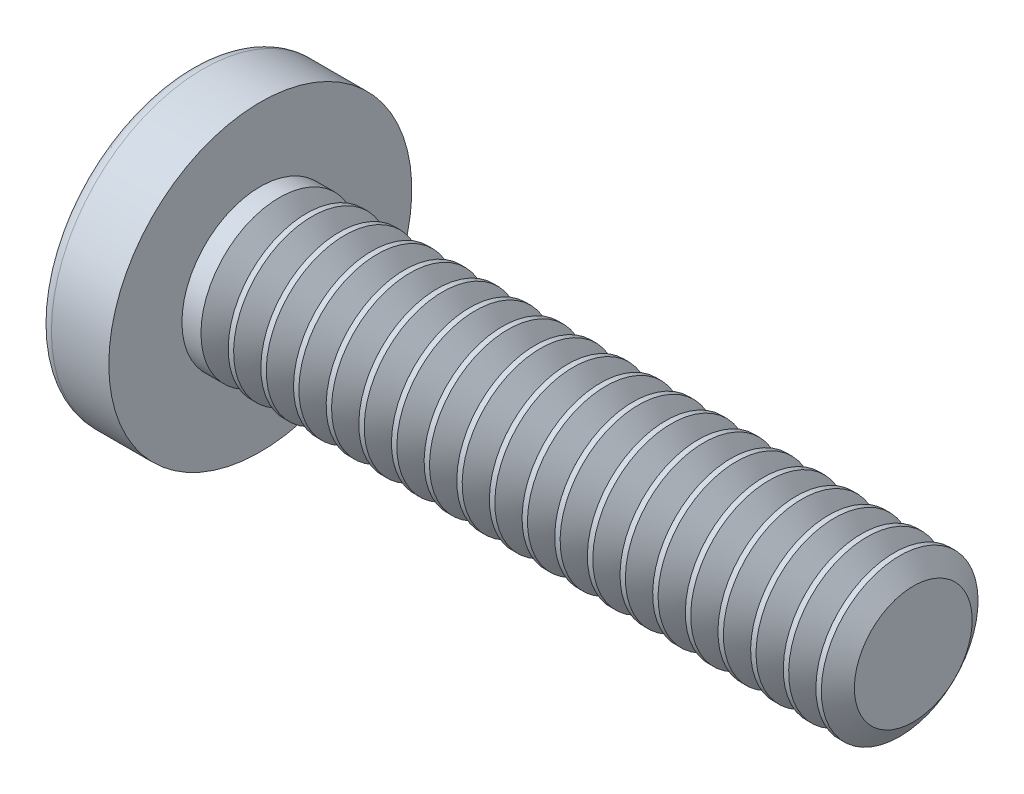
SolidWorks part; units mm, degrees
ref_plane "Plane1" through (0, 0, 0) normal (0, 0, 1) x (1, 0, 0)
ref_plane "Plane2" through (0, 0, 0) normal (0, 1, 0) x (1, 0, 0)
ref_plane "Plane3" through (0, 0, 0) normal (1, 0, 0) x (0, 0, -1)
other "Configuration Table"
sketch "BodySke" plane through (0, 0, 0) normal (0, 0, 1) x (1, 0, 0)
  line L0 (1.1176, 0.762) -> (1.1176, 1.4732)
  line L1 (1.2763, 6.35) -> (1.2764, -3.175) construction
  line L2 (-25.4, 0) -> (127, 0) construction
  line L3 (7.4676, 0) -> (0, 0)
  line L4 (1.1176, 0.762) -> (7.4676, 0.762)
  line L5 (7.4676, 0.762) -> (7.4676, 0)
  line L6 (0.5595, 1.4732) -> (1.1176, 1.4732)
  line L7 (1.1176, -0.762) -> (7.4676, -0.762) construction
  line L8 (1.1176, 6.35) -> (1.1176, -3.175) construction
  arc A0 (0.4562, 1.4202) -> (0, 0) centre (2.4384, 0) ccw
  arc A2 (0.4562, 1.4202) -> (0.5595, 1.4732) centre (0.5595, 1.3462) cw
  dimension "Head_crown_rad" = 2.4384
  dimension "Head_fillet_rad" = 0.127
  dimension "Diameter" = 1.524
  dimension "Length" = 6.35
  dimension "Head_ht" = 1.1176
  dimension "Head_dia" = 2.9464
  dimension "Advance" = 0.3175
  dimension "Thread_nom" = 6.35
revolve "Base-Revolve" add sketch "BodySke" angle 360 about L2
cosmetic thread "ThreadCosmetic" [suppressed] parameters "Thread_length"=6.0325, "Thread_minor"=1.1455
sketch "Sketch3" plane through (0, 0, 0) normal (1, 0, 0) x (0, 0, -1)
  line L0 (0.2794, -0.9652) -> (-0.2794, -0.9652)
  line L1 (0.2794, -0.9652) -> (0.2794, 0.9652)
  line L2 (-0.2794, 0.9652) -> (0.2794, 0.9652)
  line L3 (-0.2794, 0.9652) -> (-0.2794, -0.9652)
  dimension "Cross_dia" = 1.9304
  dimension "D1" = 0.9652
  dimension "Cross_width" = 0.5588
  dimension "D2" = 0.2794
ref_plane "Plane4" through (0.9652, 0, 0) normal (1, 0, 0) x (0, 0, -1)
sketch "Sketch4" plane through (0.9652, 0, 0) normal (1, 0, 0) x (0, 0, -1)
  line L0 (0.1397, -0.1397) -> (-0.1397, -0.1397)
  line L1 (0.1397, -0.1397) -> (0.1397, 0.1397)
  line L2 (-0.1397, 0.1397) -> (0.1397, 0.1397)
  line L3 (-0.1397, 0.1397) -> (-0.1397, -0.1397)
  dimension "D2" = 0.2794
  dimension "D1" = 0.2794
  dimension "D3" = 0.1397
  dimension "D4" = 0.1397
loft "Cut-Loft1" cut profiles "Sketch3", "Sketch4"
pattern_circular "CirPattern1" count 2 every 90 about axis through (0, 0, 0) along (1, 0, 0) of "Cut-Loft1"
sketch "ThdSchSke" plane through (0, 0, 0) normal (0, 0, 1) x (1, 0, 0)
  line L0 (1.4351, -0.5728) -> (1.3026, -0.762)
  line L1 (1.4351, -0.5728) -> (1.5676, -0.762)
  line L2 (1.5676, -0.762) -> (1.5676, -0.9525)
  line L3 (-3.175, 0) -> (5.1513, 0) construction
  line L5 (1.5676, -0.9525) -> (1.3026, -0.9525)
  line L6 (1.3026, -0.9525) -> (1.3026, -0.762)
  dimension "Diameter" = 1.524
  dimension "SideAngle" = 55
  dimension "VeeAngle" = 70
  dimension "Thread_minor" = 1.1455
  dimension "Overcut" = 1.905
  dimension "Start" = 1.4351
revolve "ThreadSchematic" cut sketch "ThdSchSke" angle 360 about L3
pattern_linear "ThdSchPat" count 20 spacing 0.3175 along (1, 0, 0) of "ThreadSchematic"
equation "\"D1@Sketch3\" = \"Cross_dia@Sketch3\" / 2"
equation "\"D2@Sketch3\" = \"Cross_width@Sketch3\" / 2"
equation "\"D1@Sketch4\" = \"Cross_width@Sketch3\" *.5"
equation "\"D2@Sketch4\" = \"D1@Sketch4\""
equation "\"D3@Sketch4\" = \"D1@Sketch4\" / 2"
equation "\"D4@Sketch4\" = \"D2@Sketch4\" / 2"
equation "\"Thread_length@ThreadCosmetic\" = ((sgn( (\"Length@BodySke\" - \"Advance@BodySke\" ) - \"Thread_nom@BodySke\" )-1)*( (\"Length@BodySke\" - \"Advance@BodySke\" ) - \"Thread_nom@BodySke\" ))/-2+ \"Thread_nom@BodySke\""
equation "\"Thread_minor@ThdSchSke\" = \"Thread_minor@ThreadCosmetic\""
equation "\"Diameter@ThdSchSke\" = \"Diameter@BodySke\""
equation "\"Overcut@ThdSchSke\" = \"Diameter@BodySke\" * 1.25"
equation "\"Start@ThdSchSke\" = \"Head_ht@BodySke\" + \"Length@BodySke\" - \"Thread_length@ThreadCosmetic\"  '---Non-countersunk---"
equation "\"Num_threads@ThdSchPat\" = int( \"Thread_length@ThreadCosmetic\" / \"Advance@BodySke\" + 0.999 )  + 1"
equation "\"Advance@ThdSchPat\" = \"Thread_length@ThreadCosmetic\" /  (\"Num_threads@ThdSchPat\" - 1) 'relax it"
